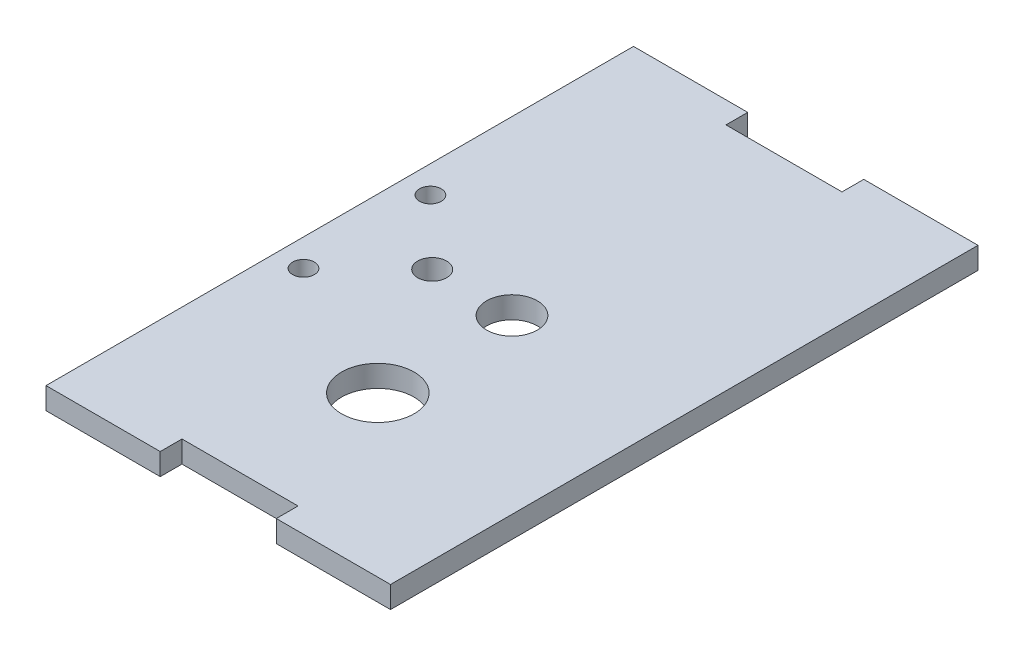
SolidWorks part; units mm, degrees
ref_plane "Alzado" through (0, 0, 0) normal (0, 0, 1) x (1, 0, 0)
ref_plane "Planta" through (0, 0, 0) normal (0, 1, 0) x (1, 0, 0)
ref_plane "Vista lateral" through (0, 0, 0) normal (1, 0, 0) x (0, 0, -1)
sketch "Croquis1" plane through (0, 0, 0) normal (0, 1, 0) x (1, 0, 0)
  line L0 (0, 0) -> (15.75, 0)
  line L1 (47.5, 0) -> (47.5, 81)
  line L2 (23.75, 3) -> (15.75, 3)
  line L3 (15.75, 3) -> (15.75, 0)
  line L4 (23.75, 3) -> (31.75, 3)
  line L5 (31.75, 3) -> (31.75, 0)
  line L6 (47.5, 40.5) -> (38.6194, 40.5) construction
  line L7 (31.75, 78) -> (31.75, 81)
  line L8 (23.75, 78) -> (31.75, 78)
  line L9 (15.75, 78) -> (15.75, 81)
  line L10 (23.75, 78) -> (15.75, 78)
  line L11 (47.5, 81) -> (31.75, 81)
  line L12 (0, 81) -> (0, 0)
  line L13 (23.75, 78) -> (23.75, 3) construction
  line L14 (38.6194, 40.5) -> (23.75, 40.5) construction
  line L15 (23.75, 40.5) -> (3.75, 40.5) construction
  line L16 (3.75, 40.5) -> (3.75, 49.25) construction
  line L17 (23.75, 40.5) -> (12.75, 40.5) construction
  line L18 (15.75, 81) -> (0, 81)
  line L19 (31.75, 0) -> (47.5, 0)
  line L20 (23.75, 40.5) -> (23.75, 22) construction
  circle A0 centre (3.75, 49.25) radius 1.5
  circle A1 centre (3.75, 31.75) radius 1.5
  circle A2 centre (12.75, 40.5) radius 2
  circle A3 centre (23.75, 22) radius 5
  circle A4 centre (23.75, 40.5) radius 3.5
  dimension "D7" = 3
  dimension "D9" = 4
  dimension "D11" = 10
  dimension "D12" = 7
  dimension "D1" = 47.5
  dimension "D2" = 81
  dimension "D3" = 8
  dimension "D4" = 8
  dimension "D5" = 20
  dimension "D6" = 8.75
  dimension "D8" = 11
  dimension "D10" = 18.5
extrude "Saliente-Extruir1" add sketch "Croquis1" along normal blind 3
